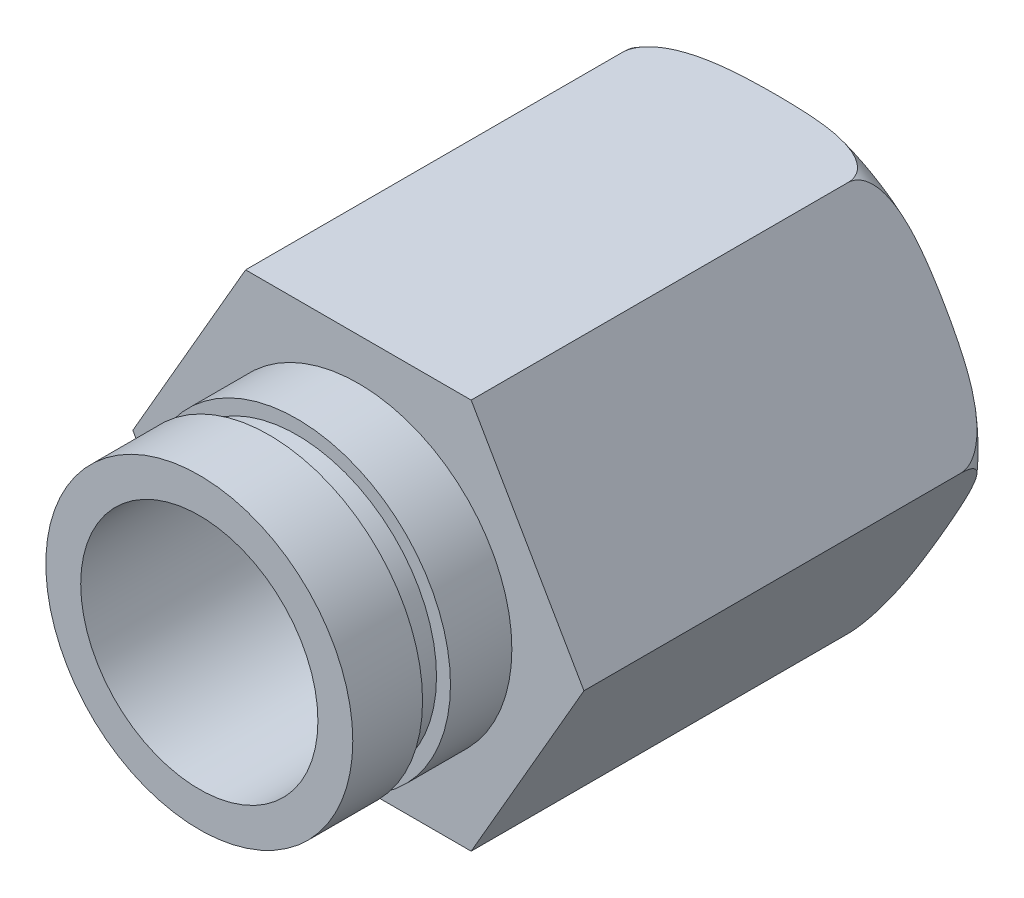
SolidWorks part; units mm, degrees
ref_plane "前视基准面" through (0, 0, 0) normal (0, 0, 1) x (1, 0, 0)
ref_plane "上视基准面" through (0, 0, 0) normal (0, 1, 0) x (1, 0, 0)
ref_plane "右视基准面" through (0, 0, 0) normal (1, 0, 0) x (0, 0, -1)
sketch "草图1" plane through (0, 0, 0) normal (0, 0, 1) x (1, 0, 0)
  line L1 (-8.0829, 0) -> (-4.0415, -7)
  line L2 (-4.0415, -7) -> (4.0415, -7)
  line L3 (4.0415, -7) -> (8.0829, 0)
  line L4 (8.0829, 0) -> (4.0415, 7)
  line L5 (4.0415, 7) -> (-4.0415, 7)
  line L6 (-4.0415, 7) -> (-8.0829, 0)
  circle A0 centre (0, 0) radius 7 construction
  dimension "D1" = 14
extrude "凸台-拉伸1" add sketch "草图1" along normal blind 15
sketch "草图2" plane through (0, 0, 15) normal (0, 0, 1) x (1, 0, 0)
  circle A0 centre (0, 0) radius 5.5
  dimension "D1" = 11
extrude "凸台-拉伸2" add sketch "草图2" along normal blind 5.7
sketch "草图3" plane through (0, 0, 20.7) normal (0, 0, 1) x (1, 0, 0)
  circle A0 centre (0, 0) radius 4.25
  dimension "D1" = 8.5
extrude "切除-拉伸1" cut sketch "草图3" against normal blind 12.7
hole_wizard "M8x1.25 螺纹孔1" positions "草图5" profile "草图4" tap size "M8x1.25" standard "Ansi Metric" end condition up to next
sketch "草图5" plane through (0, 0, 0) normal (0, 0, -1) x (-1, 0, 0)
  point P0 (0, 0)
sketch "草图4" plane through (0, 0, 0) normal (1, 0, 0) x (0, 1, 0)
  line L0 (0, 0) -> (0, 8)
  line L1 (0, 8) -> (4, 8)
  line L2 (4, 8) -> (4, 0)
  line L5 (4, 0) -> (0, 0)
  line L11 (0, -6.35) -> (0, 107.95) construction
  dimension "螺纹线主直径" = 8
  dimension "通孔螺纹孔钻头深度" = 8
sketch "草图8" plane through (0, 0, 0) normal (0, 1, 0) x (1, 0, 0)
  line L0 (-5.5, -17.2) -> (-5.5, -18.2)
  line L1 (-5.5, -18.2) -> (-5, -18.2)
  line L2 (-8.0829, -15) -> (-4.0415, -15) construction
  line L3 (-5.5, -17.2) -> (-5, -17.2)
  line L4 (-5, -18.2) -> (-5, -17.2)
  dimension "D1" = 2.2
  dimension "D2" = 1
  dimension "D3" = 0.5
  dimension "D4" = 5.5
ref_axis "基准轴2" through (0, 0, 8) along (0, 0, -1)
revolve "切除-旋转1" cut sketch "草图8" angle 360 about axis through (0, 0, 8) along (0, 0, -1)
sketch "草图9" plane through (0, 0, 0) normal (0, 1, 0) x (1, 0, 0)
  line L1 (-8.0829, 0) -> (-4.0415, 0) construction
  line L3 (-8.0829, -1.5) -> (-8.0829, 0)
  line L4 (-6.5829, 0) -> (-8.0829, 0)
  arc A1 (-6.5829, 0) -> (-8.0829, -1.5) centre (-6.5829, -1.5) ccw
  point P7 (-8.0829, 0)
  dimension "D2" = 1.5
revolve "切除-旋转2" cut sketch "草图9" angle 360 about axis through (0, 0, 8) along (0, 0, -1)
